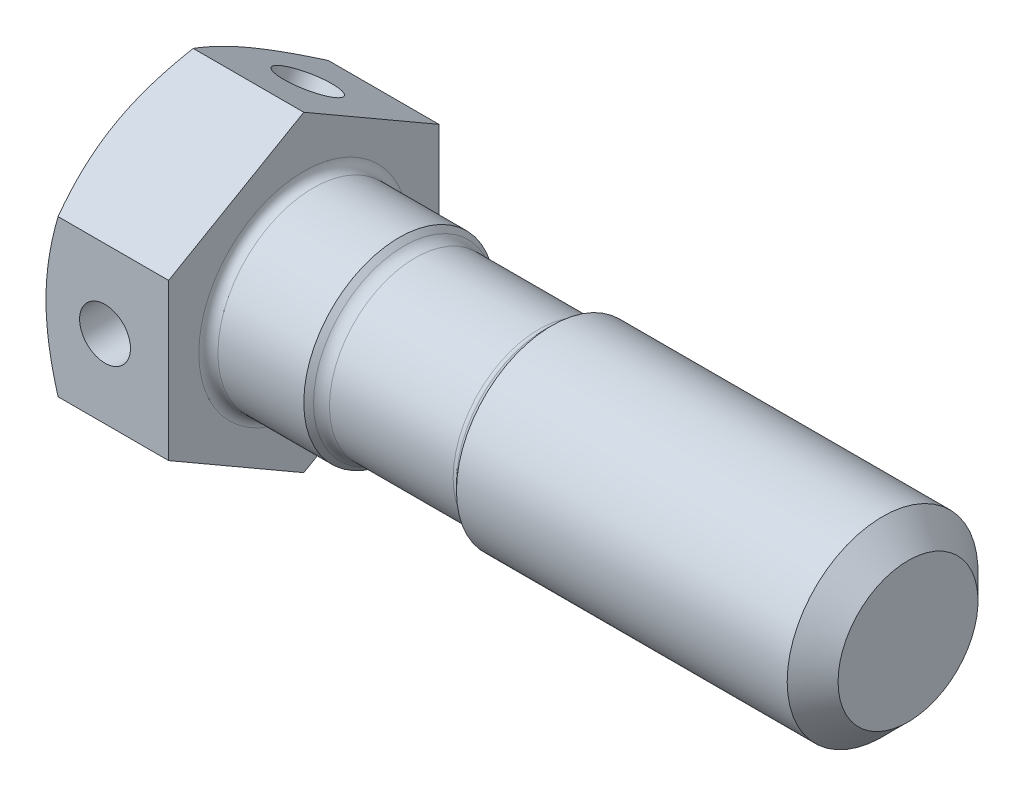
SolidWorks part; units mm, degrees
material "Простая углеродистая сталь"
ref_plane "Спереди" through (0, 0, 0) normal (0, 0, 1) x (1, 0, 0)
ref_plane "Сверху" through (0, 0, 0) normal (0, 1, 0) x (1, 0, 0)
ref_plane "Справа" through (0, 0, 0) normal (1, 0, 0) x (0, 0, -1)
other "Таблица"
sketch "Эскиз1" plane through (0, 0, 0) normal (0, 0, 1) x (1, 0, 0)
  line L0 (0, 0) -> (41.4975, 0) construction
  line L1 (0, 0) -> (0, 6)
  line L2 (0, 6) -> (6, 6)
  line L3 (6, 6) -> (6.3071, 5.6929)
  line L4 (7.0142, 5.4) -> (14.7929, 5.4)
  line L5 (15.1464, 5.5464) -> (15.6, 6)
  line L6 (15.6, 6) -> (36.4, 6)
  line L7 (38, 4.4) -> (38, 0)
  line L8 (38, 0) -> (0, 0)
  line L9 (36.4, 6) -> (38, 4.4)
  arc A0 (7.0142, 5.4) -> (6.3071, 5.6929) centre (7.0142, 6.4) cw
  arc A1 (15.1464, 5.5464) -> (14.7929, 5.4) centre (14.7929, 5.9) cw
  point P3 (38, 6)
  point P16 (15, 5.4)
  dimension "D10" = 1
  dimension "D11" = 0.5
  dimension "D1" = 12
  dimension "D2" = 10.8
  dimension "D3" = 12
  dimension "D4" = 45
  dimension "D5" = 6
  dimension "D6" = 23
  dimension "D7" = 38
  dimension "D8" = 1.6
  dimension "D9" = 45
revolve "Повернуть1" add sketch "Эскиз1" angle 360 about L0
cosmetic thread "Условное изображение резьбы1" parameters "D2"=10.072
sketch "Эскиз2" plane through (0, 0, 0) normal (-1, 0, 0) x (0, 0, 1)
  line L0 (-8.5, 0) -> (8.5, 0) construction
  line L1 (0, -9.815) -> (0, 9.815) construction
  line L3 (0, -9.815) -> (8.5, -4.9075)
  line L4 (8.5, -4.9075) -> (8.5, 4.9075)
  line L5 (8.5, 4.9075) -> (0, 9.815)
  line L6 (0, 9.815) -> (-8.5, 4.9075)
  line L7 (-8.5, 4.9075) -> (-8.5, -4.9075)
  line L8 (-8.5, -4.9075) -> (0, -9.815)
  circle A0 centre (0, 0) radius 9.815 construction
  point P6 (0, 0)
  dimension "D1" = 17
extrude "Бобышка-Вытянуть1" add sketch "Эскиз2" along normal blind 8
sketch "Эскиз3" plane through (-8, 0, 0) normal (-1, 0, 0) x (0, 0, 1)
  circle A0 centre (0, 0) radius 8
  dimension "D1" = 16
extrude "Вырез-Вытянуть1" cut sketch "Эскиз3" against normal through all draft 60 flip side to cut
fillet "Скругление1" radius 0.6 1 edges at (0, 0, 6)
sketch "Эскиз4" plane through (0, 0, 8.5) normal (0, 0, 1) x (1, 0, 0)
  line L0 (-9.9529, 0) -> (8.4534, 0) construction
  line L1 (-8, 8) -> (-8, -8) construction
  circle A0 centre (-4, 0) radius 1.6
  dimension "D1" = 3.2
  dimension "D2" = 4
extrude "Вырез-Вытянуть2" cut sketch "Эскиз4" against normal through all
sketch "Эскиз5" plane through (0, -7.3612, 4.25) normal (0, -0.866, 0.5) x (1, 0, 0)
  line L0 (-10.0003, 0) -> (5.1327, 0) construction
  line L1 (-8, 8) -> (-8, -8) construction
  circle A0 centre (-4, 0) radius 1.75
  dimension "D1" = 3.5
  dimension "D2" = 4
extrude "Вырез-Вытянуть3" cut sketch "Эскиз5" against normal through all
